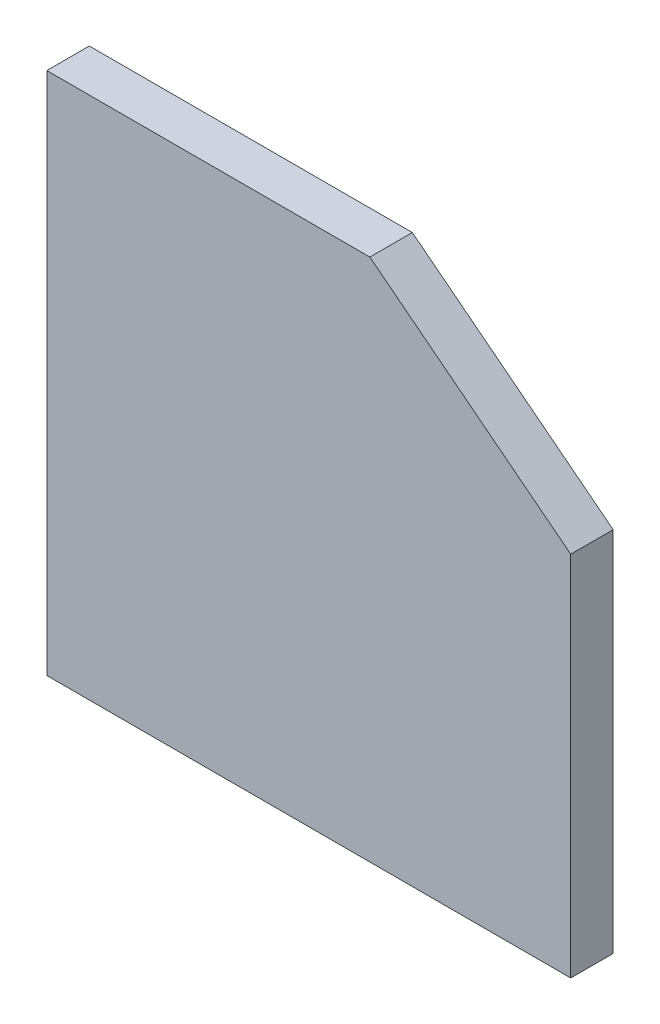
SolidWorks part; units mm, degrees
ref_plane "Front Plane" through (0, 0, 0) normal (0, 0, 1) x (1, 0, 0)
ref_plane "Top Plane" through (0, 0, 0) normal (0, 1, 0) x (1, 0, 0)
ref_plane "Right Plane" through (0, 0, 0) normal (1, 0, 0) x (0, 0, -1)
sketch "Sketch1" plane through (0, 0, 0) normal (0, 0, 1) x (1, 0, 0)
  line L0 (22.8158, 37) -> (37, 25.9181)
  line L1 (0, 0) -> (37, 0)
  line L2 (0, 0) -> (0, 37)
  line L3 (0, 37) -> (37, 37)
  line L4 (37, 0) -> (37, 37)
  dimension "D1" = 37
  dimension "D2" = 37
  dimension "D3" = 38
  dimension "D4" = 18
extrude "Boss-Extrude1" add sketch "Sketch1" along normal blind 3 contours L1 L4 L0 L3 L2
